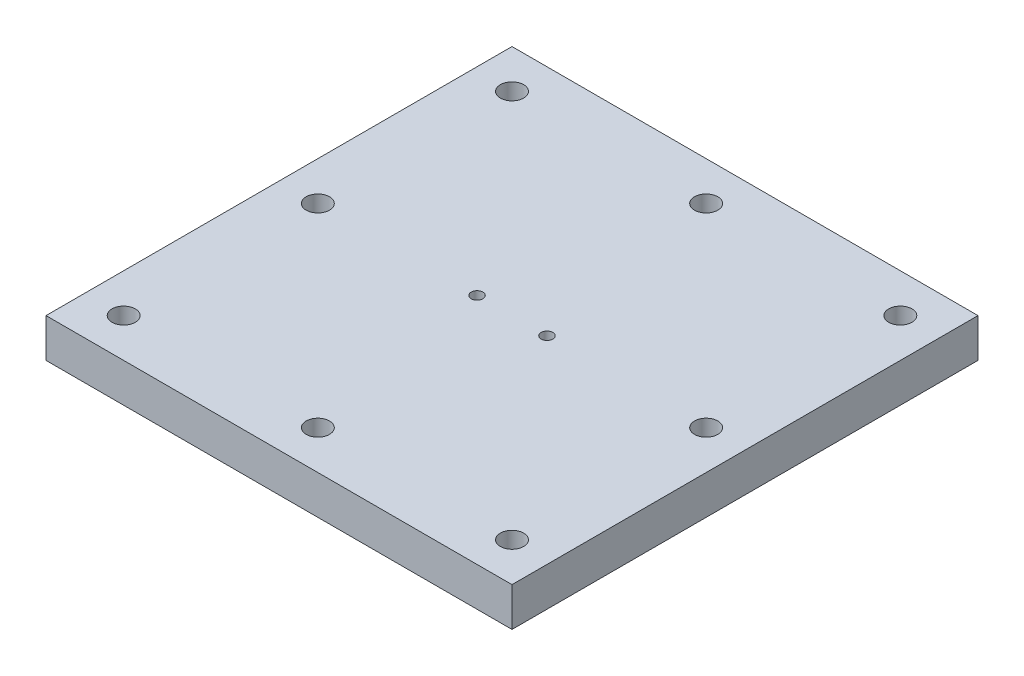
SolidWorks part; units mm, degrees
ref_plane "Front Plane" through (0, 0, 0) normal (0, 0, 1) x (1, 0, 0)
ref_plane "Top Plane" through (0, 0, 0) normal (0, 1, 0) x (1, 0, 0)
ref_plane "Right Plane" through (0, 0, 0) normal (1, 0, 0) x (0, 0, -1)
sketch "Sketch1" plane through (0, 0, 0) normal (0, 1, 0) x (1, 0, 0)
  line L1 (0, 36.4633) -> (0, -13.5367) construction
  line L2 (-21.2688, 0) -> (20.3819, 0) construction
  line L16 (-30, 30) -> (30, 30)
  line L17 (30, 30) -> (30, -30)
  line L18 (-30, -30) -> (30, -30)
  line L19 (-30, 30) -> (-30, -30)
  line L21 (-5.5, 1.5) -> (5.5, 1.5) construction
  line L22 (-5.5, 1.5) -> (-5.5, -1.5) construction
  line L23 (-5.5, -1.5) -> (5.5, -1.5) construction
  line L24 (5.5, 1.5) -> (5.5, -1.5) construction
  line L25 (-5, -5) -> (5, -5) construction
  line L26 (-5, -5) -> (-5, 5) construction
  line L27 (-5, 5) -> (5, 5) construction
  line L28 (5, -5) -> (5, 5) construction
  line L29 (-5, -5) -> (5, 5) construction
  line L30 (-5, 5) -> (5, -5) construction
  circle A4 centre (25, 25) radius 1.5
  circle A5 centre (25, -25) radius 1.5
  circle A6 centre (-25, -25) radius 1.5
  circle A7 centre (-25, 25) radius 1.5
  circle A8 centre (0, 25) radius 1.5
  circle A9 centre (25, 0) radius 1.5
  circle A10 centre (-25, 0) radius 1.5
  circle A11 centre (0, -25) radius 1.5
  circle A12 centre (-4.5, 0) radius 0.75
  circle A13 centre (4.5, 0) radius 0.75
  point P12 (0, 0)
  point P24 (30, 0)
  point P25 (0, -30)
  point P26 (0, 30)
  dimension "D9" = 4.5
  dimension "D10" = 3
  dimension "D13" = 3
  dimension "D15" = 3
  dimension "D8" = 1.5
  dimension "D2" = 11
  dimension "D3" = 3
  dimension "D4" = 1.5
  dimension "D5" = 30
  dimension "D6" = 30
  dimension "D7" = 5.5
  dimension "D11" = 5
  dimension "D12" = 5
  dimension "D14" = 5
  dimension "D16" = 5
  dimension "D17" = 10
  dimension "D18" = 10
extrude "Boss-Extrude1" add sketch "Sketch1" along normal blind 5
